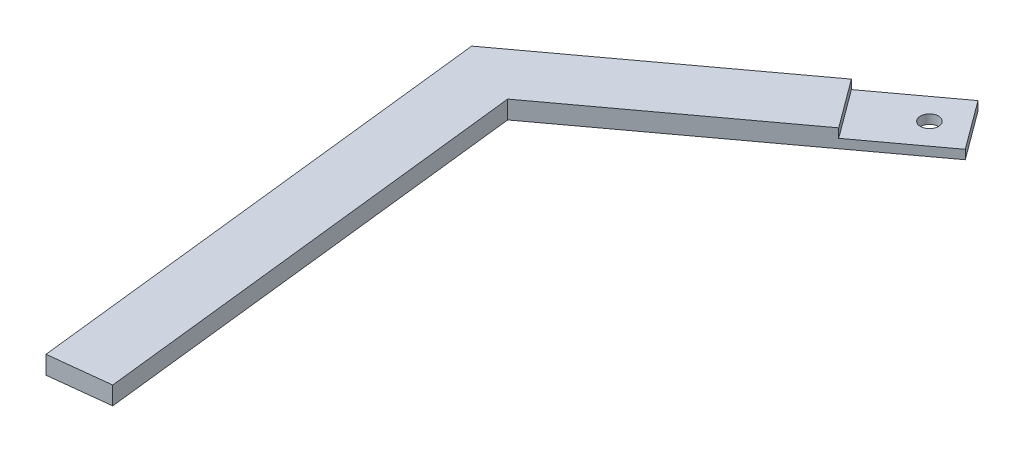
SolidWorks part; units mm, degrees
ref_plane "Front Plane" through (0, 0, 0) normal (0, 0, 1) x (1, 0, 0)
ref_plane "Top Plane" through (0, 0, 0) normal (0, 1, 0) x (1, 0, 0)
ref_plane "Right Plane" through (0, 0, 0) normal (1, 0, 0) x (0, 0, -1)
sketch "Sketch1" plane through (0, 0, 0) normal (0, 1, 0) x (1, 0, 0)
  line L0 (18.258, 29.4777) -> (-30.0156, -6.1547)
  line L2 (-19.4317, -10.7715) -> (24.1967, 21.4321)
  line L3 (24.1967, 21.4321) -> (18.258, 29.4777)
  line L4 (-30.0156, -6.1547) -> (-21.0533, -85.6511)
  line L5 (-21.0533, -85.6511) -> (-11.1162, -84.5308)
  line L6 (-11.1162, -84.5308) -> (-19.4317, -10.7715)
  point P6 (-10.4346, -87.2439)
  point P7 (-19.4612, -8.2646)
  dimension "D1" = 10
  dimension "D2" = 10
  dimension "D3" = 60
  dimension "D4" = 80
  dimension "D5" = 120
extrude "Boss-Extrude1" add sketch "Sketch1" along normal blind 3
sketch "Sketch2" plane through (0, 3, 0) normal (0, 1, 0) x (1, 0, 0)
  line L0 (18.258, 29.4777) -> (24.1967, 21.4321)
  line L1 (18.258, 29.4777) -> (6.1896, 20.5696)
  line L2 (24.1967, 21.4321) -> (12.1283, 12.524)
  line L3 (6.1896, 20.5696) -> (12.1283, 12.524)
  dimension "D1" = 15
extrude "Cut-Extrude1" cut sketch "Sketch2" against normal blind 1.5
sketch "Sketch3" plane through (0, 1.5, 0) normal (0, 1, 0) x (1, 0, 0)
  line L0 (24.1967, 21.4321) -> (18.258, 29.4777) construction
  circle A0 centre (17.2046, 22.4855) radius 1.5
  dimension "D1" = 1.5
  dimension "D2" = 5
extrude "Cut-Extrude2" cut sketch "Sketch3" against normal blind 1.5
